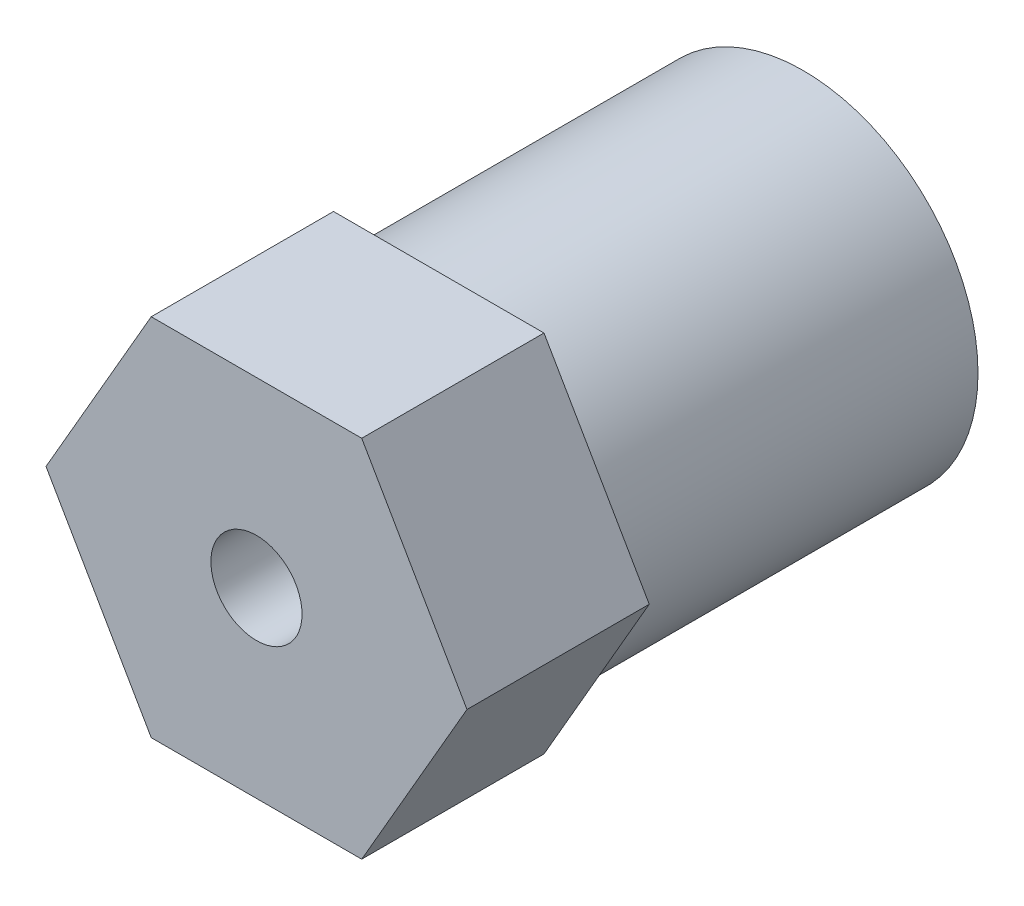
SolidWorks part; units mm, degrees
ref_plane "Front Plane" through (0, 0, 0) normal (0, 0, 1) x (1, 0, 0)
ref_plane "Top Plane" through (0, 0, 0) normal (0, 1, 0) x (1, 0, 0)
ref_plane "Right Plane" through (0, 0, 0) normal (1, 0, 0) x (0, 0, -1)
sketch "Sketch1" plane through (0, 0, 0) normal (0, 0, 1) x (1, 0, 0)
  circle A0 centre (0, 0) radius 5.75
  circle A1 centre (0, 0) radius 3
  dimension "D1" = 6
  dimension "D2" = 11.5
extrude "Boss-Extrude1" add sketch "Sketch1" along normal blind 12
sketch "Sketch2" plane through (0, 0, 12) normal (0, 0, 1) x (1, 0, 0)
  line L13 (3.4641, -6) -> (6.9282, 0)
  line L14 (6.9282, 0) -> (3.4641, 6)
  line L15 (3.4641, 6) -> (-3.4641, 6)
  line L16 (-3.4641, 6) -> (-6.9282, 0)
  line L17 (-6.9282, 0) -> (-3.4641, -6)
  line L18 (-3.4641, -6) -> (3.4641, -6)
  circle A0 centre (0, 0) radius 6 construction
  dimension "D1" = 12
extrude "Boss-Extrude2" add sketch "Sketch2" along normal blind 6
sketch "Sketch3" plane through (0, 0, 18) normal (0, 0, 1) x (1, 0, 0)
  circle A0 centre (0, 0) radius 1.5
  dimension "D1" = 3
extrude "Cut-Extrude1" cut sketch "Sketch3" against normal through all
